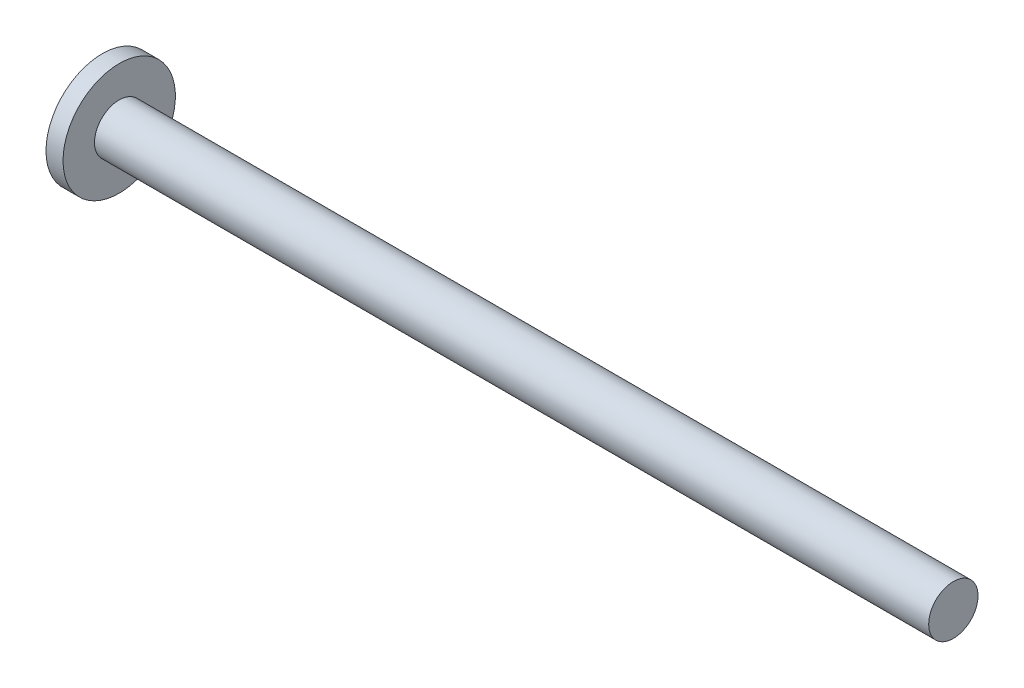
SolidWorks part; units mm, degrees
ref_plane "Front Plane" through (0, 0, 0) normal (0, 0, 1) x (1, 0, 0)
ref_plane "Top Plane" through (0, 0, 0) normal (0, 1, 0) x (1, 0, 0)
ref_plane "Right Plane" through (0, 0, 0) normal (1, 0, 0) x (0, 0, -1)
sketch "Sketch1" plane through (0, 0, 0) normal (0, 0, 1) x (1, 0, 0)
  line L0 (-80.3638, 0) -> (-29.5638, 0)
  line L1 (-29.5638, 0) -> (-29.5638, 1.4732)
  line L2 (-29.5638, 1.4732) -> (-79.3478, 1.4732)
  line L3 (-79.3478, 1.4732) -> (-79.3478, 3.3528)
  line L4 (-79.3478, 3.3528) -> (-80.3638, 3.3528)
  line L5 (-80.3638, 3.3528) -> (-80.3638, 0)
  dimension "D1" = 1.4732
  dimension "D2" = 1.016
  dimension "D3" = 50.8
  dimension "D4" = 3.3528
revolve "Revolve1" add sketch "Sketch1" angle 360 about L0
